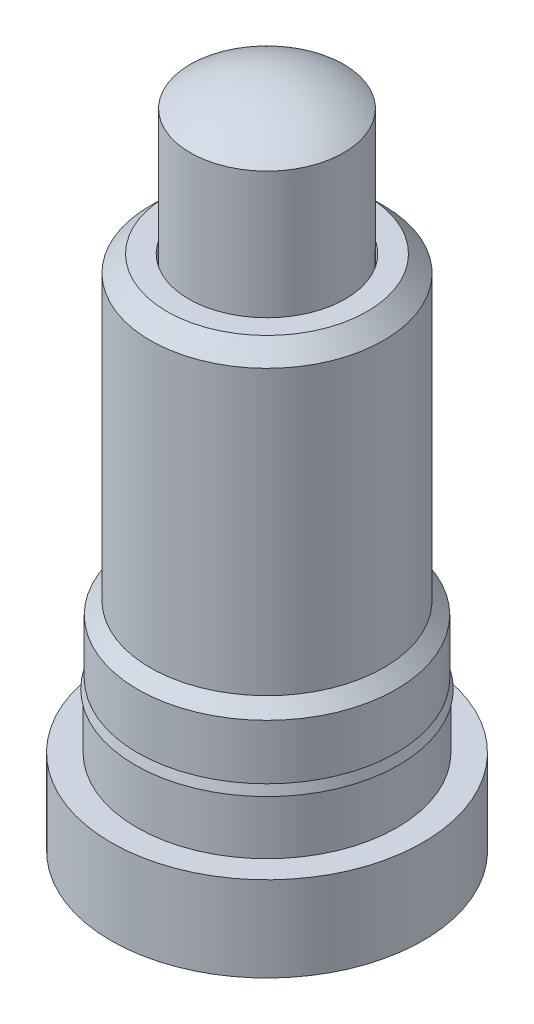
SolidWorks part; units mm, degrees
ref_plane "Front Plane" through (0, 0, 0) normal (0, 0, 1) x (1, 0, 0)
ref_plane "Top Plane" through (0, 0, 0) normal (0, 1, 0) x (1, 0, 0)
ref_plane "Right Plane" through (0, 0, 0) normal (1, 0, 0) x (0, 0, -1)
ref_axis "Axis1" through (0, -1.3833, 0) along (0, 1, 0)
sketch "Sketch1" plane through (0, 0, 0) normal (0, 0, 1) x (1, 0, 0)
  line L0 (-2.3749, 0) -> (-2.3749, 1.2954)
  line L1 (-2.3749, 1.2954) -> (-1.9812, 1.2954)
  line L2 (-1.9685, 2.2745) -> (-1.9685, 3.1115)
  line L3 (-1.9685, 3.1115) -> (-1.778, 3.302)
  line L4 (-1.1684, 6.7691) -> (-1.1684, 9.7905)
  line L5 (0, 0) -> (0, 10.16) construction
  line L6 (-2.3749, 0) -> (0, 0)
  line L8 (-1.3335, 6.604) -> (-1.3335, 5.842)
  line L9 (-1.3335, 5.842) -> (-1.0414, 5.842)
  line L10 (-1.0414, 5.842) -> (-1.0414, 8.2887)
  line L11 (-1.0414, 8.2887) -> (0, 8.89)
  line L12 (-1.1684, 6.7691) -> (-1.3335, 6.604)
  line L14 (-1.1938, 7.874) -> (-1.1938, 6.7437)
  line L16 (-1.3589, 6.5786) -> (-1.3589, 0)
  line L17 (-1.9685, 2.2745) -> (-2.0066, 2.1324)
  line L18 (-1.9812, 2.1324) -> (-1.9812, 1.2954)
  line L19 (-2.0066, 2.1324) -> (-1.9812, 2.1324)
  line L20 (-1.778, 3.302) -> (-1.778, 7.62)
  line L21 (-1.778, 7.62) -> (-1.524, 7.874)
  line L22 (-1.524, 7.874) -> (-1.1938, 7.874)
  line L24 (-1.1938, 6.7437) -> (-1.3589, 6.5786)
  arc A0 (-1.1684, 9.7905) -> (0, 10.16) centre (0, 8.128) cw construction
  arc A1 (-1.1684, 7.7585) -> (0, 8.128) centre (0, 6.096) cw construction
  dimension "D1" = 4.7498
  dimension "D6" = 60
  dimension "D18" = 2.032
  dimension "D15" = 2.032
  dimension "D2" = 1.2954
  dimension "D3" = 3.937
  dimension "D4" = 2.286
  dimension "D5" = 2.3368
  dimension "D7" = 0.127
  dimension "D8" = 1.27
  dimension "D9" = 3.556
  dimension "D10" = 0.0254
  dimension "D11" = 0.0254
  dimension "D12" = 45
  dimension "D13" = 3.302
  dimension "D14" = 7.874
  dimension "D16" = 4.0132
  dimension "D17" = 15
  dimension "D19" = 0.0254
  dimension "D20" = 0.254
  dimension "D21" = 0.762
  dimension "D22" = 2.032
  dimension "D23" = 2.667
sketch "Sketch2" plane through (0, 0, 0) normal (0, 0, 1) x (1, 0, 0)
  line L0 (-1.3589, 6.5786) -> (-1.3589, 0) construction
  line L2 (-1.1938, 7.874) -> (-1.1938, 6.7437) construction
  line L5 (-1.9685, 3.1115) -> (-1.778, 3.302) construction
  line L6 (-2.0066, 2.1324) -> (-1.9812, 2.1324) construction
  line L7 (-2.3749, 1.2954) -> (-1.9812, 1.2954) construction
  line L8 (-2.3749, 0) -> (-2.3749, 1.2954) construction
  line L9 (-2.3749, 0) -> (0, 0) construction
  line L10 (-1.3589, 6.5786) -> (-1.3589, 0)
  line L12 (-1.1938, 7.874) -> (-1.1938, 6.7437)
  line L15 (-1.9685, 3.1115) -> (-1.778, 3.302)
  line L17 (-2.3749, 1.2954) -> (-1.9812, 1.2954)
  line L18 (-2.3749, 0) -> (-2.3749, 1.2954)
  line L19 (-2.3749, 0) -> (-1.3589, 0)
  line L20 (-1.778, 3.302) -> (-1.778, 7.62) construction
  line L22 (-1.9685, 2.2745) -> (-2.0066, 2.1324) construction
  line L23 (-1.9685, 2.2745) -> (-2.0066, 2.1324)
  line L24 (-1.9685, 2.2745) -> (-1.9685, 3.1115) construction
  line L25 (-1.9685, 2.2745) -> (-1.9685, 3.1115)
  line L26 (-1.9812, 2.1324) -> (-1.9812, 1.2954) construction
  line L27 (-2.0066, 2.1324) -> (-1.9812, 2.1324)
  line L28 (-1.9812, 2.1324) -> (-1.9812, 1.2954)
  line L29 (-1.778, 3.302) -> (-1.778, 7.62)
  line L30 (-1.778, 7.62) -> (-1.524, 7.874) construction
  line L31 (-1.778, 7.62) -> (-1.524, 7.874)
  line L32 (-1.524, 7.874) -> (-1.1938, 7.874) construction
  line L33 (-1.524, 7.874) -> (-1.1938, 7.874)
  line L34 (-1.1938, 6.7437) -> (-1.3589, 6.5786) construction
  line L35 (-1.1938, 6.7437) -> (-1.3589, 6.5786)
revolve "Revolve1" add sketch "Sketch2" angle 360 about axis through (0, -1.3833, 0) along (0, 1, 0)
sketch "Sketch3" plane through (0, 0, 0) normal (0, 0, 1) x (1, 0, 0)
  line L0 (-1.1684, 6.7691) -> (-1.1684, 9.7905) construction
  line L2 (-1.3335, 6.604) -> (-1.3335, 5.842) construction
  line L3 (-1.3335, 5.842) -> (-1.0414, 5.842) construction
  line L4 (-1.0414, 5.842) -> (-1.0414, 8.2887) construction
  line L5 (-1.0414, 8.2887) -> (0, 8.89) construction
  line L6 (-1.1684, 6.7691) -> (-1.1684, 9.7905)
  line L8 (-1.3335, 6.604) -> (-1.3335, 5.842)
  line L9 (-1.3335, 5.842) -> (-1.0414, 5.842)
  line L10 (-1.0414, 5.842) -> (-1.0414, 8.2887)
  line L11 (-1.0414, 8.2887) -> (0, 8.89)
  line L12 (0, 0) -> (0, 10.16) construction
  line L13 (0, 8.89) -> (0, 10.16)
  line L14 (-1.1684, 6.7691) -> (-1.3335, 6.604) construction
  line L15 (-1.1684, 6.7691) -> (-1.3335, 6.604)
  arc A0 (0, 10.16) -> (-1.1684, 9.7905) centre (0, 8.128) ccw construction
  arc A1 (0, 10.16) -> (-1.1684, 9.7905) centre (0, 8.128) ccw
revolve "Revolve2" add sketch "Sketch3" angle 360 about axis through (0, -1.3833, 0) along (0, 1, 0)
sketch "Sketch4" plane through (0, 0, 0) normal (0, -1, 0) x (1, 0, 0)
  circle A1 centre (0, 0) radius 2.3749
  circle A2 centre (0, 0) radius 2.3749
  dimension "D1" = 0
extrude "Boss-Extrude1" add sketch "Sketch4" against normal blind 0.762
move or copy body "Max Stroke" [suppressed] bodies to move or copy 102 copy no translate (0, -2.032, 0)
move or copy body "Assembled Stroke" [suppressed] bodies to move or copy 102 copy no translate (0, -0.762, 0)
